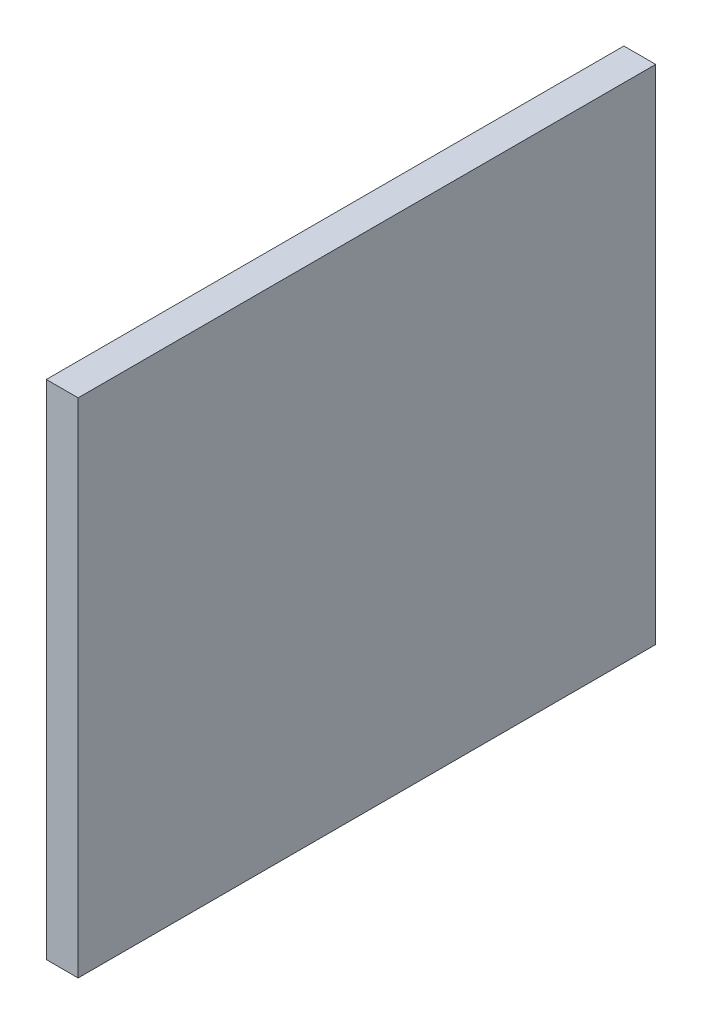
SolidWorks part; units mm, degrees
ref_plane "Front Plane" through (0, 0, 0) normal (0, 0, 1) x (1, 0, 0)
ref_plane "Top Plane" through (0, 0, 0) normal (0, 1, 0) x (1, 0, 0)
ref_plane "Right Plane" through (0, 0, 0) normal (1, 0, 0) x (0, 0, -1)
sketch "Sketch1" plane through (0, 0, 0) normal (0, 0, 1) x (1, 0, 0)
  line L0 (7625.1486, 3360.5691) -> (7625.1486, 3310.4549)
  line L1 (7621.9736, 3360.5691) -> (7621.9736, 3310.4549)
  line L2 (7621.9736, 3360.5691) -> (7625.1486, 3360.5691)
  line L3 (7625.1486, 3310.4549) -> (7621.9736, 3310.4549)
extrude "Boss-Extrude1" add sketch "Sketch1" along normal blind 57.6072
